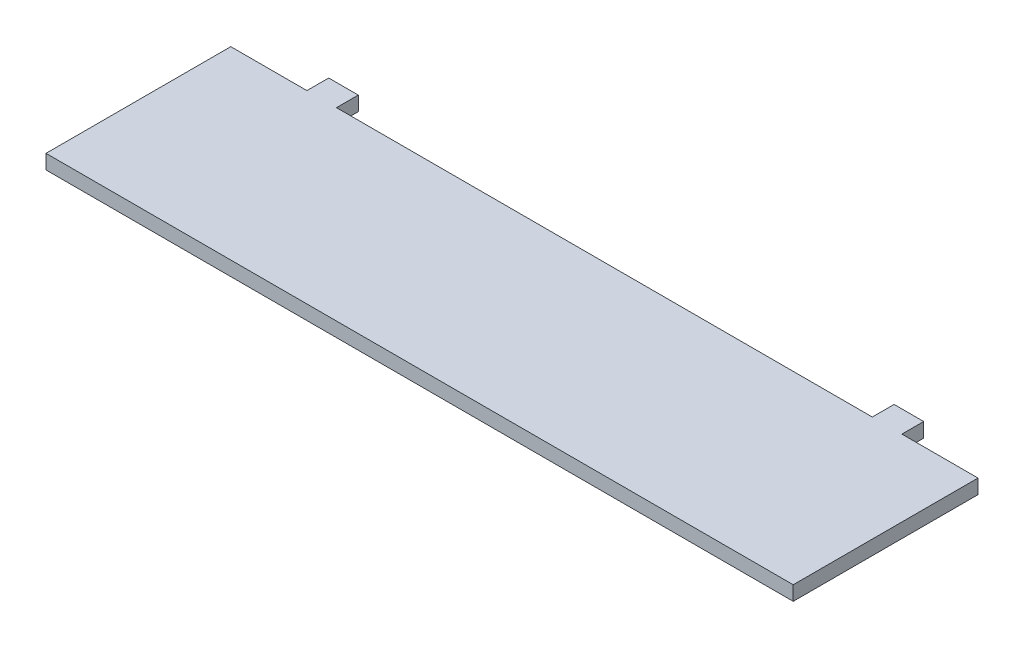
SolidWorks part; units mm, degrees
ref_plane "Front Plane" through (0, 0, 0) normal (0, 0, 1) x (1, 0, 0)
ref_plane "Top Plane" through (0, 0, 0) normal (0, 1, 0) x (1, 0, 0)
ref_plane "Right Plane" through (0, 0, 0) normal (1, 0, 0) x (0, 0, -1)
sketch "Sketch1" plane through (0, 0, 0) normal (0, 1, 0) x (1, 0, 0)
  line L1 (-41.9914, 16.3783) -> (59.1006, 16.3783)
  line L2 (-41.9914, 16.3783) -> (-41.9914, -8.6217)
  line L3 (-41.9914, -8.6217) -> (59.1006, -8.6217)
  line L4 (59.1006, 16.3783) -> (59.1006, -8.6217)
  dimension "D1" = 25
  dimension "D2" = 101.092
extrude "Boss-Extrude1" add sketch "Sketch1" along normal blind 1.95
sketch "Sketch2" plane through (0, 0, -16.3783) normal (0, 0, -1) x (-1, 0, 0)
  line L5 (-59.1006, 0) -> (41.9914, 0) construction
  line L6 (27.6937, 0) -> (31.6937, 0)
  line L7 (27.6937, 0) -> (27.6937, 1.95)
  line L9 (27.6937, 1.95) -> (31.6937, 1.95)
  line L10 (31.6937, 0) -> (31.6937, 1.95)
  line L11 (-59.1006, 1.95) -> (41.9914, 1.95) construction
  line L12 (32.1937, -0.15) -> (32.1937, 2.1) construction
  line L13 (27.1937, 2.1) -> (27.1937, -0.15) construction
  line L14 (-44.3021, -0.575) -> (-44.3021, 2.525) construction
  line L15 (-44.8021, 0) -> (-48.8021, 0)
  line L16 (-44.8021, 0) -> (-44.8021, 1.95)
  line L17 (-44.8021, 1.95) -> (-48.8021, 1.95)
  line L18 (-48.8021, 0) -> (-48.8021, 1.95)
  line L19 (-49.3021, 2.525) -> (-49.3021, -0.575) construction
  dimension "D1" = 0.5
  dimension "D2" = 0.5
  dimension "D3" = 0.5
  dimension "D4" = 0.5
extrude "Boss-Extrude2" add sketch "Sketch2" along normal blind 2.95
